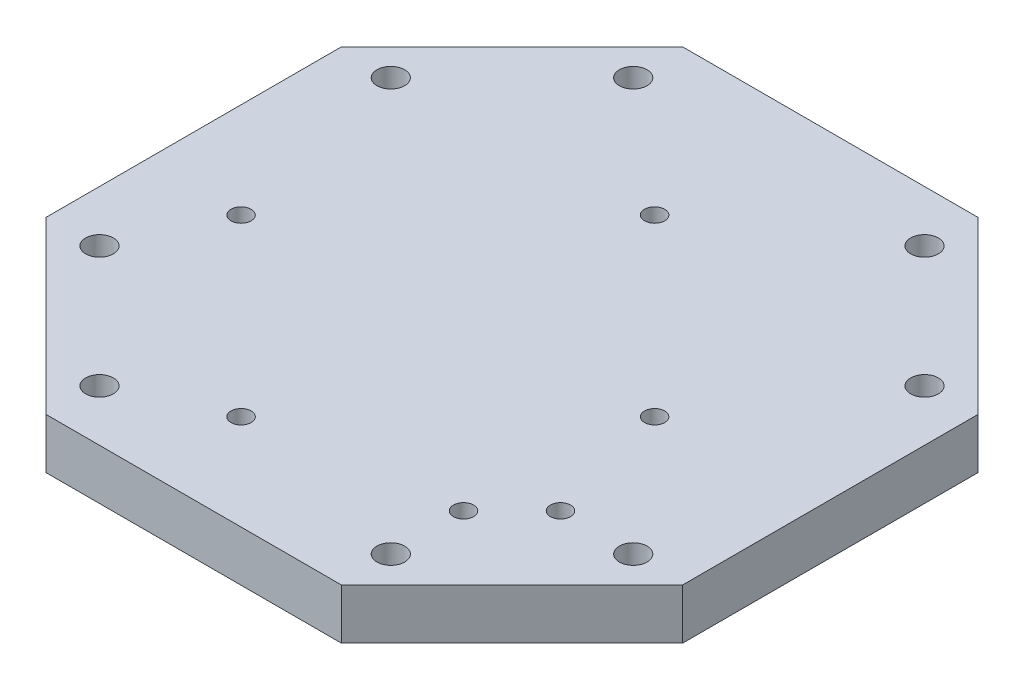
SolidWorks part; units mm, degrees
ref_plane "Plan de face" through (0, 0, 0) normal (0, 0, 1) x (1, 0, 0)
ref_plane "Plan de dessus" through (0, 0, 0) normal (0, 1, 0) x (1, 0, 0)
ref_plane "Plan de droite" through (0, 0, 0) normal (1, 0, 0) x (0, 0, -1)
sketch "Esquisse1" plane through (0, 0, 0) normal (0, 1, 0) x (1, 0, 0)
  line L0 (63.1351, -29.2914) -> (63.1351, 29.2914)
  line L1 (63.1351, 29.2914) -> (29.2914, 63.1351)
  line L2 (29.2914, 63.1351) -> (-29.2914, 63.1351)
  line L3 (-29.2914, 63.1351) -> (-63.1351, 29.2914)
  line L4 (-63.1351, 29.2914) -> (-63.1351, -29.2914)
  line L5 (-63.1351, -29.2914) -> (-29.2914, -63.1351)
  line L6 (-29.2914, -63.1351) -> (29.2914, -63.1351)
  line L7 (29.2914, -63.1351) -> (63.1351, -29.2914)
  line L8 (0, 63.1351) -> (0, -63.1351) construction
  circle A0 centre (0, 0) radius 63.1351 construction
  dimension "D1" = 58.5829
  dimension "D2" = 47.8622
extrude "Boss.-Extru.1" add sketch "Esquisse1" along normal blind 10
sketch "Esquisse3" plane through (0, 10, 0) normal (0, 1, 0) x (1, 0, 0)
  line L0 (-29.2914, 63.1351) -> (-63.1351, 29.2914) construction
  line L1 (0, 0) -> (-46.2133, 46.2133) construction
  line L2 (0, -5.5) -> (0, 5.5) construction
  line L3 (-5.5, 0) -> (5.5, 0) construction
  point P0 (-52.9308, 28.8892)
  point P1 (-28.8892, 52.9308)
  point P11 (28.8892, 52.9308)
  point P12 (52.9308, 28.8892)
  point P15 (52.9308, -28.8892)
  point P16 (28.8892, -52.9308)
  point P17 (-28.8892, -52.9308)
  point P18 (-52.9308, -28.8892)
  dimension "D1" = 7.5
  dimension "D2" = 7.5
  dimension "D3" = 17
  dimension "D4" = 17
hole_wizard "Chambrage pour tête cylindrique fendue M31" positions "Esquisse3D1" profile "Esquisse4" counterbore size "M3" standard "ISO" end condition through all
sketch3d "Esquisse3D1"
  point P0 (-28.8892, 10, -52.9308)
  point P3 (-52.9308, 10, -28.8892)
  point P6 (-52.9308, 10, 28.8892)
  point P9 (-28.8892, 10, 52.9308)
  point P12 (28.8892, 10, 52.9308)
  point P15 (52.9308, 10, 28.8892)
  point P18 (52.9308, 10, -28.8892)
  point P21 (28.8892, 10, -52.9308)
sketch "Esquisse4" plane through (-28.8892, 10, -52.9308) normal (1, 0, 0) x (0, 0, 1)
  line L0 (0, 0) -> (0, 10)
  line L1 (0, 10) -> (2, 10)
  line L3 (2, 10) -> (2, 4)
  line L4 (2, 4) -> (2.75, 4)
  line L5 (2.75, 4) -> (2.75, 0)
  line L7 (2.75, 0) -> (0, 0)
  line L11 (0, -6.35) -> (0, 107.95) construction
  dimension "Diamètre du perçage jusqu'au prochain" = 4
  dimension "Profondeur du perçage jusqu'au prochain" = 10
  dimension "Diamètre du chambrage" = 5.5
  dimension "Profondeur du chambrage" = 4
sketch "Esquisse6" plane through (0, 0, 0) normal (0, -1, 0) x (1, 0, 0)
  line L0 (-44.1942, 9.5459) -> (-9.5459, 44.1942) construction
  line L1 (-9.5459, 44.1942) -> (31.4663, 3.182) construction
  line L2 (-46.2133, 46.2133) -> (46.2133, -46.2133) construction
  line L3 (28.677, 38.2937) -> (38.2937, 28.677) construction
  line L4 (33.4854, 33.4854) -> (46.2133, 46.2133) construction
  line L5 (-63.1351, 29.2914) -> (-29.2914, 63.1351) construction
  line L6 (63.1351, -29.2914) -> (29.2914, -63.1351) construction
  line L7 (-3.182, -31.4663) -> (31.4663, 3.182) construction
  line L8 (-44.1942, 9.5459) -> (-3.182, -31.4663) construction
  line L9 (29.2914, 63.1351) -> (63.1351, 29.2914) construction
  circle A0 centre (-44.1942, 9.5459) radius 2
  circle A1 centre (-9.5459, 44.1942) radius 2
  circle A2 centre (-3.182, -31.4663) radius 2
  circle A3 centre (31.4663, 3.182) radius 2
  circle A4 centre (28.677, 38.2937) radius 2
  circle A5 centre (38.2937, 28.677) radius 2
  point P14 (-26.8701, 26.8701)
  point P19 (14.1421, -14.1421)
  dimension "D1" = 49
  dimension "D2" = 58
  dimension "D3" = 4
  dimension "D5" = 4
  dimension "D6" = 4
  dimension "D4" = 20
  dimension "D7" = 13.6
  dimension "D8" = 18
extrude "Enlèv. mat.-Extru.1" cut sketch "Esquisse6" against normal through all
